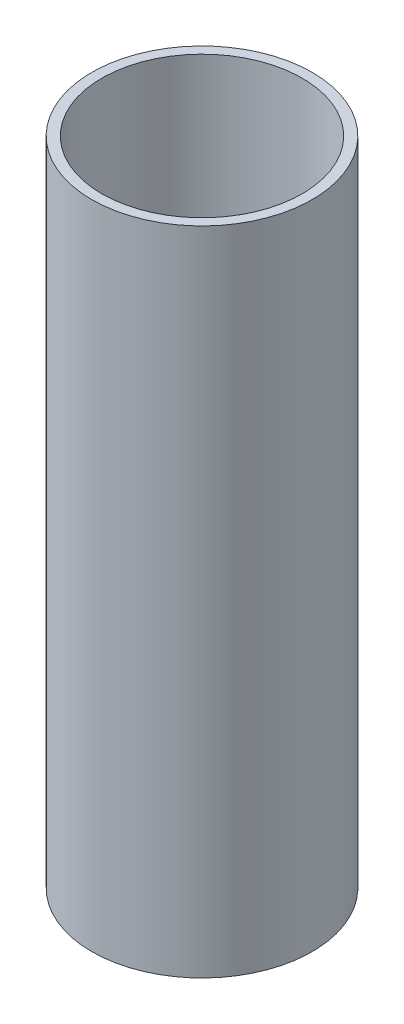
SolidWorks part; units mm, degrees
material "ｽﾃﾝﾚｽ鋼(ｸﾛﾑ)"
ref_plane "正面" through (0, 0, 0) normal (0, 0, 1) x (1, 0, 0)
ref_plane "平面" through (0, 0, 0) normal (0, 1, 0) x (1, 0, 0)
ref_plane "右側面" through (0, 0, 0) normal (1, 0, 0) x (0, 0, -1)
sketch "ｽｹｯﾁ2" plane through (0, 0, 0) normal (0, 1, 0) x (1, 0, 0)
  circle A0 centre (0, 0) radius 11
  dimension "D1" = 22
extrude "ﾎﾞｽ - 押し出し5" add sketch "ｽｹｯﾁ2" along normal blind 65 contours A0
sketch "ｽｹｯﾁ3" plane through (0, 65, 0) normal (0, 1, 0) x (1, 0, 0)
  circle A0 centre (0, 0) radius 10
  dimension "D1" = 20
extrude "ｶｯﾄ - 押し出し1" cut sketch "ｽｹｯﾁ3" against normal blind 64
